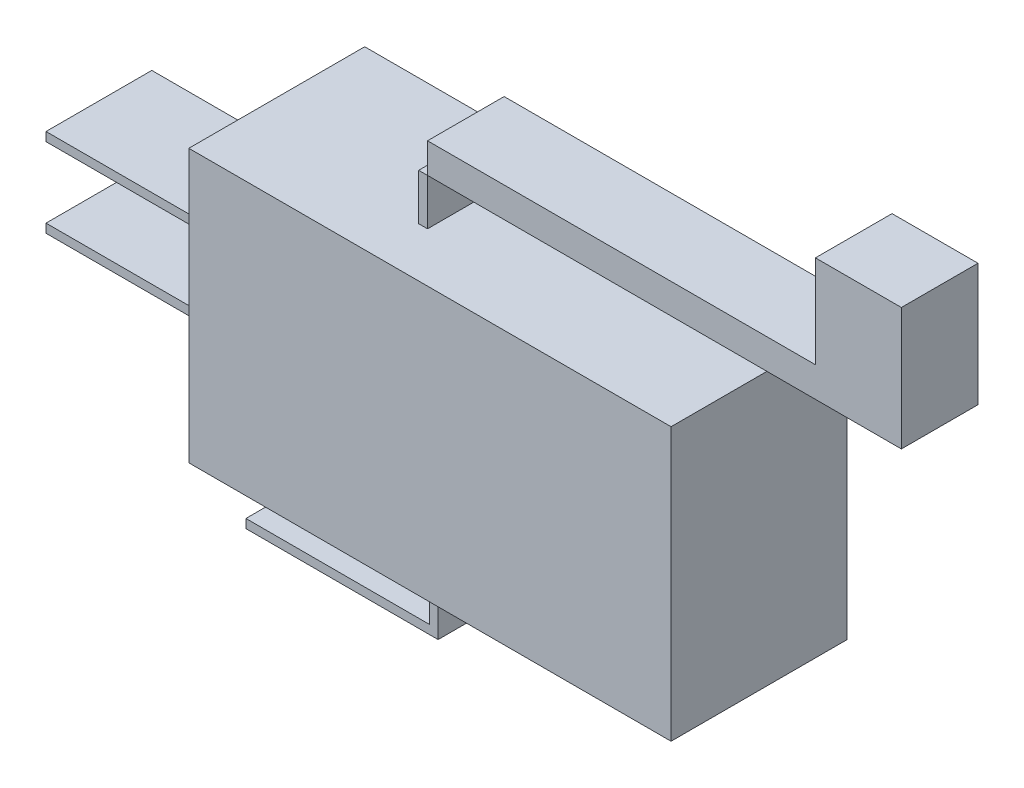
SolidWorks part; units mm, degrees
ref_plane "Front Plane" through (0, 0, 0) normal (0, 0, 1) x (1, 0, 0)
ref_plane "Top Plane" through (0, 0, 0) normal (0, 1, 0) x (1, 0, 0)
ref_plane "Right Plane" through (0, 0, 0) normal (1, 0, 0) x (0, 0, -1)
sketch "Sketch1" plane through (0, 0, 0) normal (0, 0, 1) x (1, 0, 0)
  line L1 (0, 0) -> (27.7876, 0)
  line L2 (0, 0) -> (0, 15.6972)
  line L3 (0, 15.6972) -> (27.7876, 15.6972)
  line L4 (27.7876, 0) -> (27.7876, 15.6972)
  dimension "D1" = 27.7876
  dimension "D2" = 15.6972
extrude "Boss-Extrude1" add sketch "Sketch1" along normal blind 10.1346
sketch "Sketch2" plane through (0, 0, 0) normal (-1, 0, 0) x (0, 0, 1)
  line L0 (0, 7.8486) -> (0, 9.8806) construction
  line L1 (0, 15.6972) -> (0, 0) construction
  line L2 (0, 7.8486) -> (0, 5.8166) construction
  line L3 (0, 9.8806) -> (2.0066, 9.8806) construction
  line L4 (0, 5.8166) -> (2.0066, 5.8166)
  line L6 (2.0066, 9.8806) -> (8.1026, 9.8806)
  line L7 (2.0066, 9.8806) -> (2.0066, 10.3886)
  line L8 (2.0066, 10.3886) -> (8.1026, 10.3886)
  line L9 (8.1026, 9.8806) -> (8.1026, 10.3886)
  line L10 (2.0066, 5.8166) -> (8.1026, 5.8166)
  line L11 (2.0066, 5.8166) -> (2.0066, 5.3086)
  line L12 (2.0066, 5.3086) -> (8.1026, 5.3086)
  line L13 (8.1026, 5.8166) -> (8.1026, 5.3086)
  dimension "D1" = 2.032
  dimension "D2" = 2.032
  dimension "D3" = 2.0066
  dimension "D4" = 2.0066
  dimension "D5" = 6.096
  dimension "D6" = 6.096
  dimension "D7" = 0.508
  dimension "D8" = 0.508
extrude "Boss-Extrude2" add sketch "Sketch2" along normal blind 10.2616 contours L8 L9 L6 L7 | L10 L13 L12 L11
sketch "Sketch4" plane through (0, 15.6972, 0) normal (0, 1, 0) x (1, 0, 0)
  line L0 (0, -5.0673) -> (10.3886, -5.0673) construction
  line L1 (0, -10.1346) -> (0, 0) construction
  line L2 (10.3886, -5.0673) -> (10.3886, -7.2771) construction
  line L4 (10.3886, -7.2771) -> (10.8966, -7.2771)
  line L5 (10.3886, -7.2771) -> (10.3886, -2.8575)
  line L6 (10.3886, -2.8575) -> (10.8966, -2.8575)
  line L7 (10.8966, -7.2771) -> (10.8966, -2.8575)
  dimension "D1" = 10.3886
  dimension "D2" = 2.2098
  dimension "D3" = 4.4196
  dimension "D4" = 0.508
extrude "Boss-Extrude3" add sketch "Sketch4" along normal blind 2.667
sketch "Sketch5" plane through (10.8966, 0, 0) normal (1, 0, 0) x (0, 0, -1)
  line L1 (-7.2771, 18.3642) -> (-2.8625, 18.3642)
  line L2 (-7.2771, 18.3642) -> (-7.2771, 25.4254)
  line L3 (-7.2771, 25.4254) -> (-2.8625, 25.4254)
  line L4 (-2.8625, 18.3642) -> (-2.8625, 25.4254)
  dimension "D1" = 7.0612
extrude "Boss-Extrude4" add sketch "Sketch5" along normal blind 27.305 separate body
sketch "Sketch6" plane through (0, 25.4254, 0) normal (0, 1, 0) x (1, 0, 0)
  line L0 (38.2016, -7.2771) -> (10.8966, -7.2771) construction
  line L1 (33.2486, -7.2771) -> (10.8966, -7.2771)
  line L2 (33.2486, -7.2771) -> (33.2486, -2.8625)
  line L3 (33.2486, -2.8625) -> (10.8966, -2.8625)
  line L4 (10.8966, -7.2771) -> (10.8966, -2.8625)
  dimension "D1" = 22.352
extrude "Cut-Extrude1" cut sketch "Sketch6" against normal blind 5.334
sketch "Sketch7" plane through (0, 0, 0) normal (0, -1, 0) x (1, 0, 0)
  line L0 (27.7876, 5.0673) -> (12.3444, 5.0673) construction
  line L1 (27.7876, 10.1346) -> (27.7876, 0) construction
  line L2 (12.3444, 5.0673) -> (12.3444, 8.1153) construction
  line L4 (12.3444, 8.1153) -> (11.8364, 8.1153)
  line L5 (12.3444, 8.1153) -> (12.3444, 2.0193)
  line L6 (12.3444, 2.0193) -> (11.8364, 2.0193)
  line L7 (11.8364, 8.1153) -> (11.8364, 2.0193)
  dimension "D1" = 15.4432
  dimension "D2" = 3.048
  dimension "D3" = 6.096
  dimension "D4" = 0.508
extrude "Boss-Extrude5" add sketch "Sketch7" along normal blind 3.6576
sketch "Sketch8" plane through (11.8364, 0, 0) normal (-1, 0, 0) x (0, 0, 1)
  line L0 (2.0193, -3.6576) -> (2.0193, 0) construction
  line L1 (8.1153, -3.6576) -> (2.0193, -3.6576)
  line L2 (8.1153, -3.6576) -> (8.1153, -3.1496)
  line L3 (8.1153, -3.1496) -> (2.0193, -3.1496)
  line L4 (2.0193, -3.6576) -> (2.0193, -3.1496)
  dimension "D1" = 0.508
extrude "Boss-Extrude6" add sketch "Sketch8" along normal blind 10.5664
